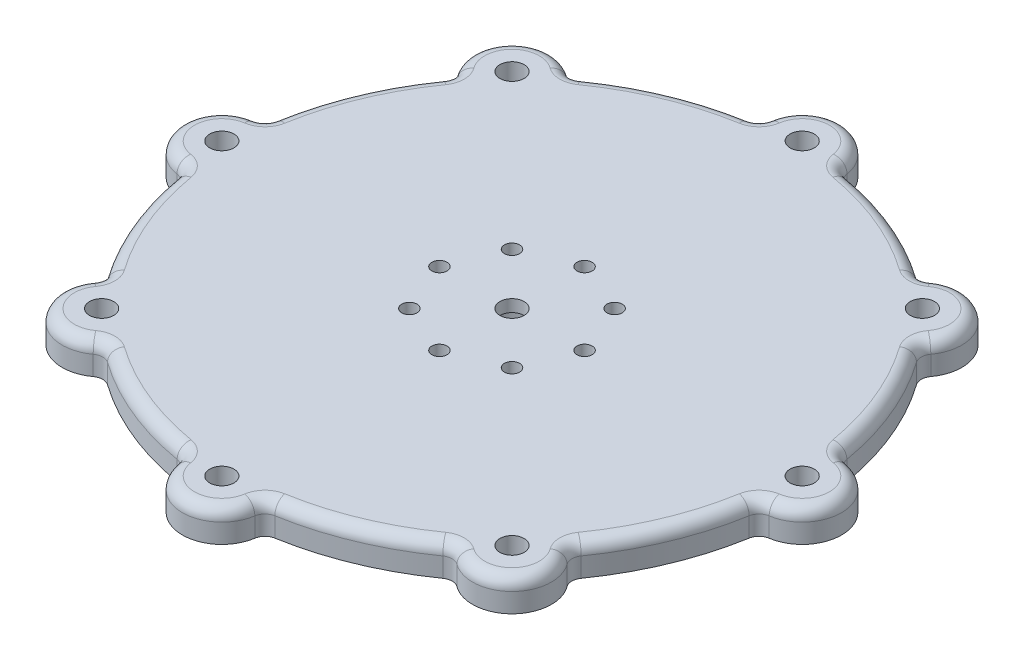
SolidWorks part; units mm, degrees
ref_plane "Front Plane" through (0, 0, 0) normal (0, 0, 1) x (1, 0, 0)
ref_plane "Top Plane" through (0, 0, 0) normal (0, 1, 0) x (1, 0, 0)
ref_plane "Right Plane" through (0, 0, 0) normal (1, 0, 0) x (0, 0, -1)
sketch "Sketch1" plane through (0, 0, 0) normal (0, 1, 0) x (1, 0, 0)
  line L0 (0, 0) -> (0, 76.2) construction
  line L1 (0, 0) -> (0, -19.05) construction
  circle A0 centre (0, 0) radius 7.9375
  circle A1 centre (0, 0) radius 76.2 construction
  circle A2 centre (0, 76.2) radius 10.35 construction
  circle A3 centre (13.3701, 78.2408) radius 3.175 construction
  circle A4 centre (-13.3701, 78.2408) radius 3.175 construction
  arc A5 (-12.8353, 75.1112) -> (-53.8815, 53.8815) centre (0, 0) ccw
  arc A6 (-10.2315, 77.7618) -> (10.2315, 77.7618) centre (0, 76.2) cw
  arc A7 (10.2315, 77.7618) -> (12.8353, 75.1112) centre (13.3701, 78.2408) ccw
  arc A8 (-10.2315, 77.7618) -> (-12.8353, 75.1112) centre (-13.3701, 78.2408) cw
  circle A9 centre (0, 76.2) radius 3.175
  arc A10 (44.0357, 62.1876) -> (0, 76.2) centre (0, 0) ccw
  arc A11 (47.7511, 62.2206) -> (44.0357, 62.1876) centre (45.8705, 64.7787) cw
  arc A12 (47.7511, 62.2206) -> (62.2206, 47.7511) centre (53.8815, 53.8815) cw
  circle A13 centre (53.8815, 53.8815) radius 3.175
  arc A14 (62.2206, 47.7511) -> (62.1876, 44.0357) centre (64.7787, 45.8705) ccw
  arc A15 (75.1112, 12.8353) -> (53.8815, 53.8815) centre (0, 0) ccw
  arc A16 (77.7618, 10.2315) -> (75.1112, 12.8353) centre (78.2408, 13.3701) cw
  arc A17 (77.7618, 10.2315) -> (77.7618, -10.2315) centre (76.2, 0) cw
  circle A18 centre (76.2, 0) radius 3.175
  arc A19 (77.7618, -10.2315) -> (75.1112, -12.8353) centre (78.2408, -13.3701) ccw
  arc A20 (62.1876, -44.0357) -> (76.2, 0) centre (0, 0) ccw
  arc A21 (62.2206, -47.7511) -> (62.1876, -44.0357) centre (64.7787, -45.8705) cw
  arc A22 (62.2206, -47.7511) -> (47.7511, -62.2206) centre (53.8815, -53.8815) cw
  circle A23 centre (53.8815, -53.8815) radius 3.175
  arc A24 (47.7511, -62.2206) -> (44.0357, -62.1876) centre (45.8705, -64.7787) ccw
  arc A25 (12.8353, -75.1112) -> (53.8815, -53.8815) centre (0, 0) ccw
  arc A26 (10.2315, -77.7618) -> (12.8353, -75.1112) centre (13.3701, -78.2408) cw
  arc A27 (10.2315, -77.7618) -> (-10.2315, -77.7618) centre (0, -76.2) cw
  circle A28 centre (0, -76.2) radius 3.175
  arc A29 (-10.2315, -77.7618) -> (-12.8353, -75.1112) centre (-13.3701, -78.2408) ccw
  arc A30 (-44.0357, -62.1876) -> (0, -76.2) centre (0, 0) ccw
  arc A31 (-47.7511, -62.2206) -> (-44.0357, -62.1876) centre (-45.8705, -64.7787) cw
  arc A32 (-47.7511, -62.2206) -> (-62.2206, -47.7511) centre (-53.8815, -53.8815) cw
  circle A33 centre (-53.8815, -53.8815) radius 3.175
  arc A34 (-62.2206, -47.7511) -> (-62.1876, -44.0357) centre (-64.7787, -45.8705) ccw
  arc A35 (-75.1112, -12.8353) -> (-53.8815, -53.8815) centre (0, 0) ccw
  arc A36 (-77.7618, -10.2315) -> (-75.1112, -12.8353) centre (-78.2408, -13.3701) cw
  arc A37 (-77.7618, -10.2315) -> (-77.7618, 10.2315) centre (-76.2, 0) cw
  circle A39 centre (-76.2, 0) radius 3.175
  arc A40 (-77.7618, 10.2315) -> (-75.1112, 12.8353) centre (-78.2408, 13.3701) ccw
  arc A41 (-62.1876, 44.0357) -> (-76.2, 0) centre (0, 0) ccw
  arc A42 (-62.2206, 47.7511) -> (-62.1876, 44.0357) centre (-64.7787, 45.8705) cw
  arc A44 (-62.2206, 47.7511) -> (-47.7511, 62.2206) centre (-53.8815, 53.8815) cw
  circle A45 centre (0, -19.05) radius 2
  circle A46 centre (-13.4704, -13.4704) radius 2
  circle A47 centre (-19.05, 0) radius 2
  circle A48 centre (-13.4704, 13.4704) radius 2
  circle A49 centre (0, 19.05) radius 2
  circle A50 centre (13.4704, 13.4704) radius 2
  circle A53 centre (-53.8815, 53.8815) radius 3.175
  arc A54 (-47.7511, 62.2206) -> (-44.0357, 62.1876) centre (-45.8705, 64.7787) ccw
  circle A55 centre (19.05, 0) radius 2
  circle A56 centre (13.4704, -13.4704) radius 2
  point P81 (0, 0)
  point P91 (0, 0)
  dimension "D1" = 15.875
  dimension "D2" = 152.4
  dimension "D3" = 6.35
  dimension "D4" = 6.35
  dimension "D5" = 20.7
  dimension "D8" = 6.35
  dimension "D10" = 4
  dimension "D6" = 76.2
  dimension "D11" = 19.05
  dimension "D7" = 45
  dimension "D9" = 8
  dimension "D12" = 8
extrude "Boss-Extrude1" add sketch "Sketch1" along normal blind 5.08
sketch "Sketch2" plane through (0, 5.08, 0) normal (0, 1, 0) x (1, 0, 0)
  line L0 (0, 0) -> (0, 76.2) construction
  circle A0 centre (0, 0) radius 76.2 construction
  circle A1 centre (0, 0) radius 3.175
  circle A2 centre (0, 76.2) radius 3.175
  circle A3 centre (0, 76.2) radius 10.35 construction
  circle A4 centre (13.3701, 78.2408) radius 3.175 construction
  circle A5 centre (-13.3701, 78.2408) radius 3.175 construction
  circle A6 centre (0, 19.05) radius 2
  circle A7 centre (13.4704, 13.4704) radius 2
  circle A8 centre (19.05, 0) radius 2
  circle A9 centre (13.4704, -13.4704) radius 2
  circle A10 centre (0, -19.05) radius 2
  circle A11 centre (-13.4704, -13.4704) radius 2
  arc A14 (-12.8353, 75.1112) -> (-53.8815, 53.8815) centre (0, 0) ccw
  arc A15 (10.2315, 77.7618) -> (-10.2315, 77.7618) centre (0, 76.2) ccw
  arc A16 (-10.2315, 77.7618) -> (-12.8353, 75.1112) centre (-13.3701, 78.2408) cw
  arc A17 (10.2315, 77.7618) -> (12.8353, 75.1112) centre (13.3701, 78.2408) ccw
  arc A18 (44.0357, 62.1876) -> (0, 76.2) centre (0, 0) ccw
  arc A19 (47.7511, 62.2206) -> (44.0357, 62.1876) centre (45.8705, 64.7787) cw
  arc A20 (62.2206, 47.7511) -> (47.7511, 62.2206) centre (53.8815, 53.8815) ccw
  circle A21 centre (53.8815, 53.8815) radius 3.175
  arc A22 (62.2206, 47.7511) -> (62.1876, 44.0357) centre (64.7787, 45.8705) ccw
  arc A23 (75.1112, 12.8353) -> (53.8815, 53.8815) centre (0, 0) ccw
  arc A24 (77.7618, 10.2315) -> (75.1112, 12.8353) centre (78.2408, 13.3701) cw
  arc A25 (77.7618, -10.2315) -> (77.7618, 10.2315) centre (76.2, 0) ccw
  circle A26 centre (76.2, 0) radius 3.175
  arc A27 (77.7618, -10.2315) -> (75.1112, -12.8353) centre (78.2408, -13.3701) ccw
  arc A28 (62.1876, -44.0357) -> (76.2, 0) centre (0, 0) ccw
  arc A29 (62.2206, -47.7511) -> (62.1876, -44.0357) centre (64.7787, -45.8705) cw
  arc A30 (47.7511, -62.2206) -> (62.2206, -47.7511) centre (53.8815, -53.8815) ccw
  circle A31 centre (53.8815, -53.8815) radius 3.175
  arc A32 (47.7511, -62.2206) -> (44.0357, -62.1876) centre (45.8705, -64.7787) ccw
  arc A33 (12.8353, -75.1112) -> (53.8815, -53.8815) centre (0, 0) ccw
  arc A34 (10.2315, -77.7618) -> (12.8353, -75.1112) centre (13.3701, -78.2408) cw
  arc A35 (-10.2315, -77.7618) -> (10.2315, -77.7618) centre (0, -76.2) ccw
  circle A36 centre (0, -76.2) radius 3.175
  arc A37 (-10.2315, -77.7618) -> (-12.8353, -75.1112) centre (-13.3701, -78.2408) ccw
  arc A38 (-44.0357, -62.1876) -> (0, -76.2) centre (0, 0) ccw
  arc A39 (-47.7511, -62.2206) -> (-44.0357, -62.1876) centre (-45.8705, -64.7787) cw
  arc A40 (-62.2206, -47.7511) -> (-47.7511, -62.2206) centre (-53.8815, -53.8815) ccw
  circle A41 centre (-53.8815, -53.8815) radius 3.175
  arc A42 (-62.2206, -47.7511) -> (-62.1876, -44.0357) centre (-64.7787, -45.8705) ccw
  circle A43 centre (-19.05, 0) radius 2
  circle A44 centre (-13.4704, 13.4704) radius 2
  arc A45 (-75.1112, -12.8353) -> (-53.8815, -53.8815) centre (0, 0) ccw
  arc A47 (-77.7618, -10.2315) -> (-75.1112, -12.8353) centre (-78.2408, -13.3701) cw
  arc A48 (-77.7618, 10.2315) -> (-77.7618, -10.2315) centre (-76.2, 0) ccw
  circle A49 centre (-76.2, 0) radius 3.175
  arc A50 (-77.7618, 10.2315) -> (-75.1112, 12.8353) centre (-78.2408, 13.3701) ccw
  arc A52 (-62.1876, 44.0357) -> (-76.2, 0) centre (0, 0) ccw
  arc A53 (-62.2206, 47.7511) -> (-62.1876, 44.0357) centre (-64.7787, 45.8705) cw
  arc A54 (-47.7511, 62.2206) -> (-62.2206, 47.7511) centre (-53.8815, 53.8815) ccw
  circle A55 centre (-53.8815, 53.8815) radius 3.175
  arc A56 (-47.7511, 62.2206) -> (-44.0357, 62.1876) centre (-45.8705, 64.7787) ccw
  point P22 (0, 0)
  point P63 (0, 0)
  dimension "D2" = 152.4
  dimension "D4" = 6.35
  dimension "D5" = 20.7
  dimension "D12" = 8
  dimension "D1" = 6.35
  dimension "D6" = 6.35
  dimension "D7" = 6.35
  dimension "D8" = 4
  dimension "D3" = 76.2
  dimension "D9" = 19.05
  dimension "D11" = 45
  dimension "D10" = 8
extrude "Boss-Extrude2" add sketch "Sketch2" along normal blind 3.175
fillet "Fillet1" radius 3.175 32 edges at (-45.8987, 8.255, 61.6039) (-61.2001, 8.255, 61.2001) (-61.6039, 8.255, 45.8987) (-76.0158, 8.255, 11.1052) (-86.55, 8.255, 0) (-61.6039, 8.255, -45.8987) (-61.2001, 8.255, -61.2001) (-29.1605, 8.255, -70.3996) (-11.1052, 8.255, -76.0158) (0, 8.255, -86.55) (11.1052, 8.255, -76.0158) (29.1605, 8.255, -70.3996) (45.8987, 8.255, -61.6039) (61.2001, 8.255, -61.2001) (61.6039, 8.255, -45.8987) (70.3996, 8.255, -29.1605) (76.0158, 8.255, -11.1052) (86.55, 8.255, 0) (76.0158, 8.255, 11.1052) (70.3996, 8.255, 29.1605) (61.6039, 8.255, 45.8987) (61.2001, 8.255, 61.2001) (45.8987, 8.255, 61.6039) (29.1605, 8.255, 70.3996) (11.1052, 8.255, 76.0158) (0, 8.255, 86.55) (-11.1052, 8.255, 76.0158) (-29.1605, 8.255, 70.3996) (-70.3996, 8.255, 29.1605) (-76.0158, 8.255, -11.1052) (-70.3996, 8.255, -29.1605) (-45.8987, 8.255, -61.6039)
equation "\"D1@Sketch1\"=\"bearing outer diam@arm.assembly\""
equation "\"D2@Sketch1\"=\"base diam@arm.assembly\"+2*\"med wall@arm.assembly\""
equation "\"D3@Sketch1\"=\"med wall@arm.assembly\""
equation "\"D4@Sketch1\"=\"med wall@arm.assembly\""
equation "\"D5@Sketch1\" = 2 * \"med wall@Arm.Assembly\" + \"1/4 threaded insert hole diam@Arm.Assembly\""
equation "\"D6@Sketch1\"=\"base diam@arm.assembly\"/2+\"med wall@arm.assembly\""
equation "\"D7@Sketch1\"=360/\"base screw num@arm.assembly\""
equation "\"D8@Sketch1\"=\"1/4 bolt@arm.assembly\""
equation "\"D9@Sketch1\"=\"base screw num@arm.assembly\""
equation "\"D10@Sketch1\"=\"3mm threaded insert hole diam@arm.assembly\""
equation "\"D11@Sketch1\"=\"med wall@Arm.Assembly\" * 3"
equation "\"D12@Sketch1\"=\"base screw num@arm.assembly\""
equation "\"D1@Boss-Extrude1\"=\"bearing height@arm.assembly\""
equation "\"D1@Sketch2\"=\"1/4 bolt@arm.assembly\""
equation "\"D2@Sketch2\"=\"base diam@arm.assembly\"+2*\"med wall@arm.assembly\""
equation "\"D3@Sketch2\"=\"base diam@arm.assembly\"/2+\"med wall@arm.assembly\""
equation "\"D4@Sketch2\"=\"1/4 bolt@arm.assembly\""
equation "\"D5@Sketch2\"=\"1/4 threaded insert hole diam@arm.assembly\"+2*\"med wall@arm.assembly\""
equation "\"D6@Sketch2\"=\"med wall@arm.assembly\""
equation "\"D7@Sketch2\"=\"med walL@arm.assembly\""
equation "\"D8@Sketch2\"=\"3mm threaded insert hole diam@arm.assembly\""
equation "\"D9@Sketch2\"=\"med wall@arm.assembly\"*3"
equation "\"D10@Sketch2\"=\"base screw num@arm.assembly\""
equation "\"D11@Sketch2\"=360/\"base screw num@arm.assembly\""
equation "\"D12@Sketch2\"=\"base screw num@arm.assembly\""
equation "\"D1@Boss-Extrude2\"=\"thin wall@arm.assembly\""
equation "\"D1@Fillet1\" = \"thin wall@Arm.Assembly\""
